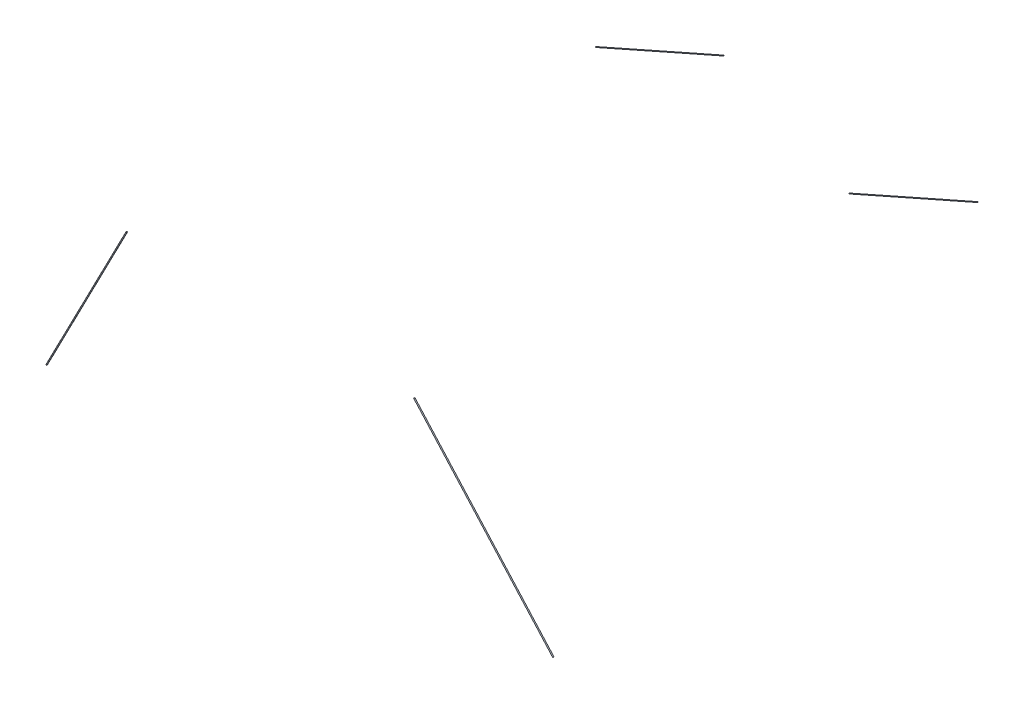
SolidWorks part; units mm, degrees
ref_plane "Front Plane" through (0, 0, 0) normal (0, 0, 1) x (1, 0, 0)
ref_plane "Top Plane" through (0, 0, 0) normal (0, 1, 0) x (1, 0, 0)
ref_plane "Right Plane" through (0, 0, 0) normal (1, 0, 0) x (0, 0, -1)
sketch3d "3DSketch1"
  line L0 (285.4746, 350.6152, -782.7736) -> (285.4746, 189.7202, -1071.1221) construction
  line L1 (285.4746, 350.6152, -782.7736) -> (285.4746, 189.7202, -1071.1221)
sweep "Sweep1" add path "3DSketch1" circular profile diameter 1.5875 parameters "D3"=1.5875
sketch3d "3DSketch2"
  line L0 (323.5012, 479.7094, 234.1998) -> (569.868, 64.8109, 167.8044)
  circle A0 centre (321.1585, 478.6294, 234.1998) radius 2.5797 construction
  point P2 (454.5432, -88.088, 276.4627)
  point P3 (0, 0, 0)
  point P4 (319.6684, 469.2217, 234.1998)
  point P6 (0, 0, 0)
  point P9 (321.1585, 478.6294, 231.6201)
sweep "Sweep2" add path "3DSketch2" circular profile diameter 2.3813 parameters "D3"=2.3813
ref_plane "Plane1" through (0, 0, 0) normal (1, 0, 0) x (0, 0, -1)
mirror "Mirror1" about plane through (0, 0, 0) normal (1, 0, 0) of bodies 101 102
